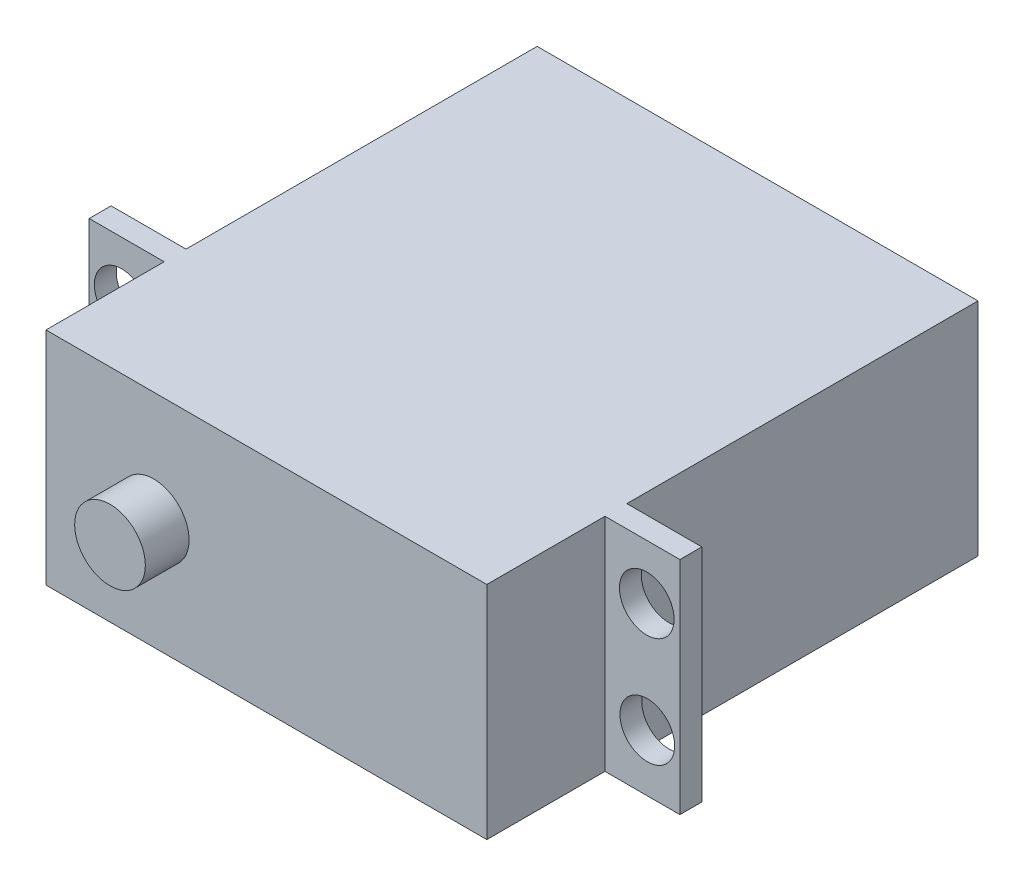
SolidWorks part; units mm, degrees
ref_plane "Plan de face" through (0, 0, 0) normal (0, 0, 1) x (1, 0, 0)
ref_plane "Plan de dessus" through (0, 0, 0) normal (0, 1, 0) x (1, 0, 0)
ref_plane "Plan de droite" through (0, 0, 0) normal (1, 0, 0) x (0, 0, -1)
sketch "Esquisse1" plane through (0, 0, 0) normal (0, 0, 1) x (1, 0, 0)
  line L1 (0, 15.5912) -> (40.3, 15.5912)
  line L2 (0, 15.5912) -> (0, -4.6088)
  line L3 (0, -4.6088) -> (40.3, -4.6088)
  line L4 (40.3, 15.5912) -> (40.3, -4.6088)
  dimension "D1" = 40.3
  dimension "D2" = 20.2
extrude "Boss.-Extru.1" add sketch "Esquisse1" along normal blind 32.1
sketch "Esquisse2" plane through (0, 0, 32.1) normal (0, 0, 1) x (1, 0, 0)
  line L0 (0, -4.6088) -> (40.3, -4.6088) construction
  line L1 (-6.85, 15.5912) -> (47.15, 15.5912)
  line L2 (-6.85, 15.5912) -> (-6.85, -4.6088)
  line L3 (-6.85, -4.6088) -> (47.15, -4.6088)
  line L4 (47.15, 15.5912) -> (47.15, -4.6088)
  line L5 (40.3, 15.5912) -> (0, 15.5912) construction
  line L6 (0, 15.5912) -> (0, -4.6088) construction
  dimension "D1" = 54
  dimension "D2" = 0
  dimension "D3" = 0
  dimension "D4" = 6.85
extrude "Boss.-Extru.2" add sketch "Esquisse2" along normal blind 2
sketch "Esquisse3" plane through (0, 0, 34.1) normal (0, 0, 1) x (1, 0, 0)
  line L0 (-6.85, -4.6088) -> (47.15, -4.6088) construction
  line L1 (0, -4.6088) -> (40.3, -4.6088)
  line L2 (0, -4.6088) -> (0, 15.5912)
  line L3 (0, 15.5912) -> (40.3, 15.5912)
  line L4 (40.3, -4.6088) -> (40.3, 15.5912)
  line L5 (47.15, 15.5912) -> (-6.85, 15.5912) construction
  line L6 (47.15, -4.6088) -> (47.15, 15.5912) construction
  line L7 (-6.85, 15.5912) -> (-6.85, -4.6088) construction
  dimension "D1" = 6.85
  dimension "D2" = 6.85
extrude "Boss.-Extru.3" add sketch "Esquisse3" along normal blind 10.8
sketch "Esquisse4" plane through (0, 0, 44.9) normal (0, 0, 1) x (1, 0, 0)
  line L0 (40.3, 15.5912) -> (0, 15.5912) construction
  line L3 (0, 15.5912) -> (0, -4.6088) construction
  circle A0 centre (9.85, 5.4912) radius 3.2301
  dimension "D1" = 10.1
  dimension "D2" = 9.85
extrude "Boss.-Extru.4" add sketch "Esquisse4" along normal blind 4
sketch "Esquisse5" plane through (0, 0, 34.1) normal (0, 0, 1) x (1, 0, 0)
  line L4 (47.15, 15.5912) -> (40.3, 15.5912) construction
  line L5 (0, 15.5912) -> (-6.85, 15.5912) construction
  line L8 (47.15, -4.6088) -> (47.15, 15.5912) construction
  circle A0 centre (-3.88, 10.5912) radius 2.5
  circle A1 centre (-3.8321, 0.5913) radius 2.5
  circle A2 centre (44.12, 10.5912) radius 2.5
  circle A3 centre (44.1679, 0.5913) radius 2.5
  dimension "D1" = 5
  dimension "D2" = 5
  dimension "D4" = 10
  dimension "D6" = 5
  dimension "D8" = 5
  dimension "D9" = 5
  dimension "D10" = 48
  dimension "D3" = 10
  dimension "D5" = 48
  dimension "D7" = 5
  dimension "D11" = 3.03
extrude "Enlèv. mat.-Extru.1" cut sketch "Esquisse5" against normal blind 4
